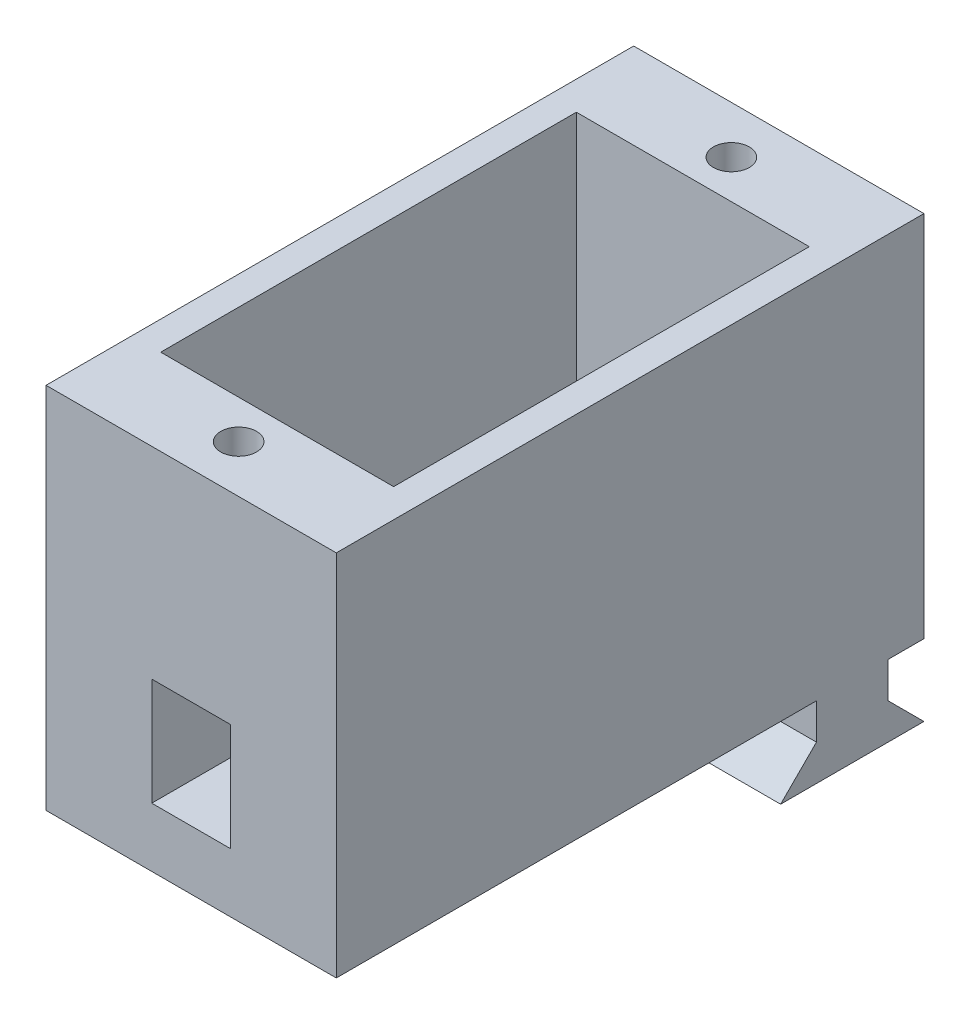
SolidWorks part; units mm, degrees
material "ABS"
ref_plane "Front Plane" through (0, 0, 0) normal (0, 0, 1) x (1, 0, 0)
ref_plane "Top Plane" through (0, 0, 0) normal (0, 1, 0) x (1, 0, 0)
ref_plane "Right Plane" through (0, 0, 0) normal (1, 0, 0) x (0, 0, -1)
sketch "Sketch1" plane through (0, 0, 0) normal (0, 1, 0) x (1, 0, 0)
  line L1 (-93.1, -10.9) -> (-76.9, -10.9)
  line L2 (-93.1, -10.9) -> (-93.1, 21.9)
  line L3 (-93.1, 21.9) -> (-76.9, 21.9)
  line L4 (-76.9, -10.9) -> (-76.9, 21.9)
extrude "Boss-Extrude1" add sketch "Sketch1" along normal mid plane 20.55 from offset 56.075
sketch "Sketch2" plane through (0, 0, 0) normal (1, 0, 0) x (0, 0, -1)
  line L0 (19.9, 46.3) -> (15.9, 46.3)
  line L1 (15.9, 46.3) -> (15.9, 43.8)
  line L2 (15.9, 43.8) -> (13.9, 41.8)
  line L3 (13.9, 41.8) -> (21.9, 41.8)
  line L4 (21.9, 41.8) -> (19.9, 43.8)
  line L5 (19.9, 43.8) -> (19.9, 46.3)
extrude "Boss-Extrude2" add sketch "Sketch2" along normal mid plane 16.2 from offset 85
sketch "Sketch3" plane through (0, 0, 0) normal (0, 1, 0) x (1, 0, 0)
  line L1 (-91.5, -6.1) -> (-78.5, -6.1)
  line L2 (-91.5, -6.1) -> (-91.5, 17.1)
  line L3 (-91.5, 17.1) -> (-78.5, 17.1)
  line L4 (-78.5, -6.1) -> (-78.5, 17.1)
extrude "Cut-Extrude1" cut sketch "Sketch3" against normal mid plane 17.25 from offset 57.725
sketch "Sketch4" plane through (0, 0, 0) normal (0, 1, 0) x (1, 0, 0)
  circle A0 centre (-85, 19.25) radius 1
extrude "Cut-Extrude2" cut sketch "Sketch4" against normal mid plane 6 from offset 63.35
sketch "Sketch5" plane through (0, 0, 0) normal (0, 1, 0) x (1, 0, 0)
  circle A0 centre (-85, -8.25) radius 1
extrude "Cut-Extrude3" cut sketch "Sketch5" against normal mid plane 6 from offset 63.35
sketch "Sketch6" plane through (0, 0, 0) normal (0, 1, 0) x (1, 0, 0)
  circle A0 centre (-85, 0) radius 3.15
extrude "Cut-Extrude4" cut sketch "Sketch6" against normal mid plane 2.6 from offset 47.1
sketch "Sketch7" plane through (0, 0, 0) normal (0, 0, 1) x (1, 0, 0)
  line L1 (-87.2, 49.1) -> (-82.8, 49.1)
  line L2 (-87.2, 49.1) -> (-87.2, 55.1)
  line L3 (-87.2, 55.1) -> (-82.8, 55.1)
  line L4 (-82.8, 49.1) -> (-82.8, 55.1)
extrude "Cut-Extrude5" cut sketch "Sketch7" against normal mid plane 4.8 from offset 8.5
